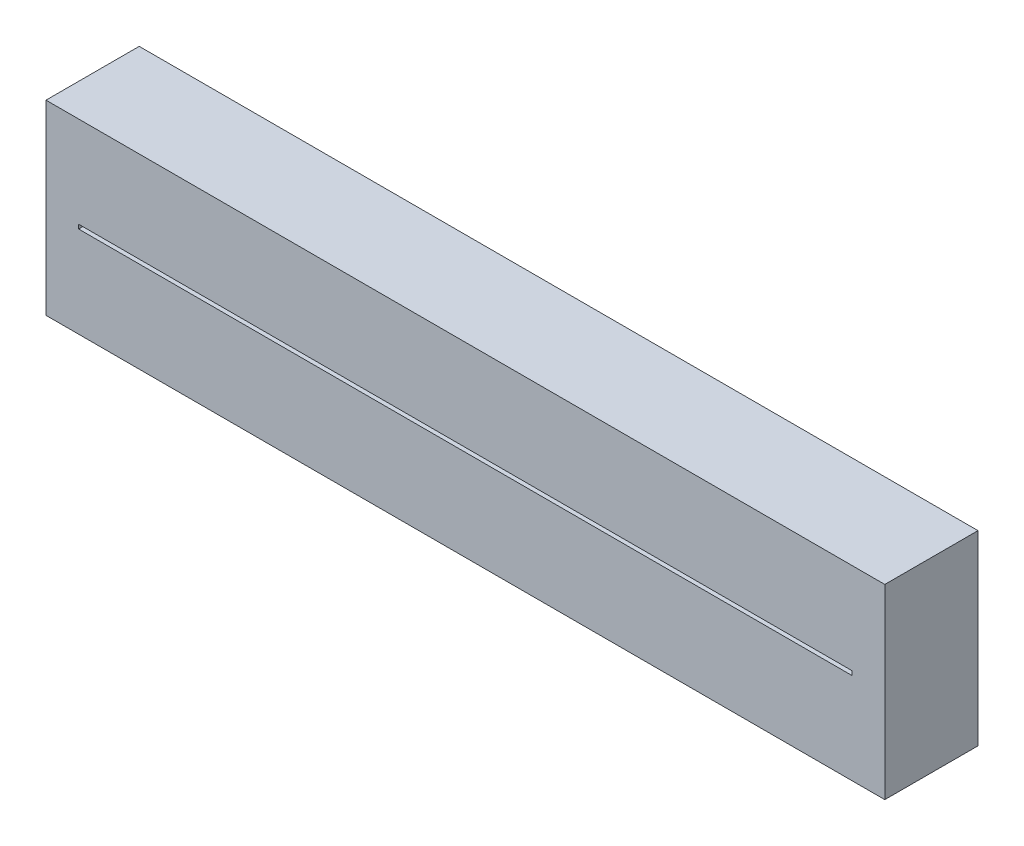
SolidWorks part; units mm, degrees
ref_plane "Front Plane" through (0, 0, 0) normal (0, 0, 1) x (1, 0, 0)
ref_plane "Top Plane" through (0, 0, 0) normal (0, 1, 0) x (1, 0, 0)
ref_plane "Right Plane" through (0, 0, 0) normal (1, 0, 0) x (0, 0, -1)
sketch "Sketch1" plane through (0, 0, 0) normal (0, 0, 1) x (1, 0, 0)
  line L1 (-45, 10) -> (45, 10)
  line L2 (-45, 10) -> (-45, -10)
  line L3 (-45, -10) -> (45, -10)
  line L4 (45, 10) -> (45, -10)
  line L5 (-45, 10) -> (45, -10) construction
  line L6 (-45, -10) -> (45, 10) construction
  point P0 (0, 0)
  dimension "D1" = 20
  dimension "D2" = 90
extrude "Boss-Extrude1" add sketch "Sketch1" along normal blind 10
sketch "Sketch2" plane through (0, 0, 10) normal (0, 0, 1) x (1, 0, 0)
  line L1 (-41.5, 0.225) -> (41.5, 0.225)
  line L2 (-41.5, 0.225) -> (-41.5, -0.225)
  line L3 (-41.5, -0.225) -> (41.5, -0.225)
  line L4 (41.5, 0.225) -> (41.5, -0.225)
  line L5 (-41.5, 0.225) -> (41.5, -0.225) construction
  line L6 (-41.5, -0.225) -> (41.5, 0.225) construction
  point P0 (0, 0)
  dimension "D1" = 83
  dimension "D2" = 0.45
extrude "Cut-Extrude1" cut sketch "Sketch2" against normal blind 5
